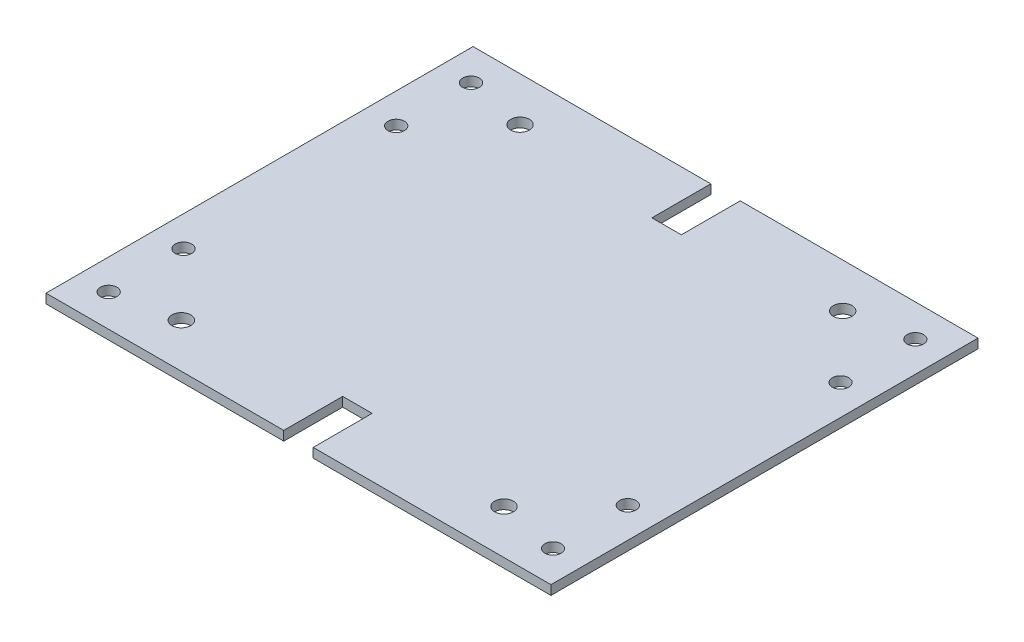
SolidWorks part; units mm, degrees
material "Acrylic (Medium-high impact)"
ref_plane "Front Plane" through (0, 0, 0) normal (0, 0, 1) x (1, 0, 0)
ref_plane "Top Plane" through (0, 0, 0) normal (0, 1, 0) x (1, 0, 0)
ref_plane "Right Plane" through (0, 0, 0) normal (1, 0, 0) x (0, 0, -1)
sketch "Sketch1" plane through (0, 0, 0) normal (0, 1, 0) x (1, 0, 0)
  line L0 (69.775, 125) -> (69.775, 20) construction
  line L1 (0, 0) -> (64.775, 0)
  line L3 (0, 145) -> (64.775, 145)
  line L5 (0, 72.5) -> (139.55, 72.5) construction
  line L7 (64.775, 130) -> (64.775, 125)
  line L8 (64.775, 125) -> (74.775, 125)
  line L9 (74.775, 145) -> (74.775, 125)
  line L11 (64.775, 20) -> (74.775, 20)
  line L14 (64.775, 130) -> (64.775, 145)
  line L15 (0, 145) -> (-15.95, 145)
  line L17 (0, 0) -> (-15.95, 0)
  line L18 (-15.95, 145) -> (-15.95, 0)
  line L19 (139.55, 145) -> (155.5, 145)
  line L22 (155.5, 145) -> (155.5, 0)
  line L28 (74.775, 145) -> (139.55, 145)
  line L30 (64.775, 20) -> (64.775, 0)
  line L31 (74.775, 20) -> (74.775, 0)
  line L32 (74.775, 0) -> (155.5, 0)
  line L33 (74.775, 0) -> (74.775, 20)
  circle A0 centre (15, 130) radius 3.175
  circle A1 centre (124.55, 130) radius 3.175
  circle A2 centre (15, 15) radius 3.175
  circle A3 centre (124.55, 15) radius 3.175
  circle A4 centre (-5.663, 134.0145) radius 2.794
  circle A5 centre (-5.663, 108.6145) radius 2.794
  circle A6 centre (145.213, 134.0145) radius 2.794
  circle A7 centre (145.213, 108.6145) radius 2.794
  circle A8 centre (-5.663, 36.3855) radius 2.794
  circle A9 centre (-5.663, 10.9855) radius 2.794
  circle A10 centre (145.213, 10.9855) radius 2.794
  circle A11 centre (145.213, 36.3855) radius 2.794
  point P14 (64.775, 127.5)
  point P15 (64.775, 17.5)
  dimension "D7" = 6.35
  dimension "D3" = 25.4
  dimension "D9" = 10.287
  dimension "D14" = 145
  dimension "D20" = 5.588
  dimension "D21" = 5.588
  dimension "D1" = 139.55
  dimension "D2" = 145
  dimension "D4" = 10
  dimension "D5" = 5
  dimension "D6" = 10.9855
  dimension "D8" = 15
  dimension "D10" = 171.45
  dimension "D11" = 15.95
  dimension "D12" = 15.95
  dimension "D13" = 10.287
  dimension "D15" = 20
  dimension "D16" = 15
  dimension "D17" = 5
  dimension "D18" = 85.725
  dimension "D19" = 15.95
  dimension "D22" = 54.775
extrude "Boss-Extrude3" add sketch "Sketch1" along normal blind 3.175 contours A3 | A1 | A0 | A2 | L11 L30 L1 L17 L18 L15 L3 L14 L7 L8 L9 L28 L19 L22 L32 L31 | A4 | A5 | A8 | A9 | A10 | A11 | A7 | A6
